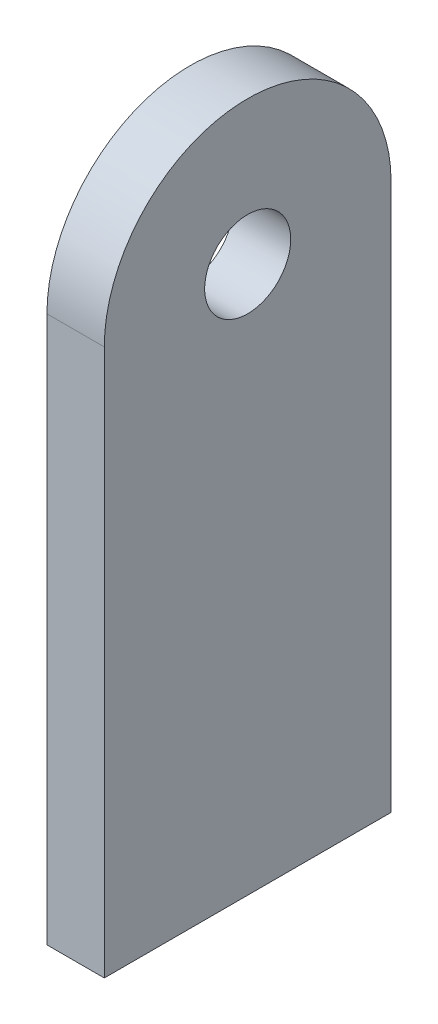
SolidWorks part; units mm, degrees
ref_plane "Front Plane" through (0, 0, 0) normal (0, 0, 1) x (1, 0, 0)
ref_plane "Top Plane" through (0, 0, 0) normal (0, 1, 0) x (1, 0, 0)
ref_plane "Right Plane" through (0, 0, 0) normal (1, 0, 0) x (0, 0, -1)
sketch "Sketch1" plane through (0, 0, 0) normal (1, 0, 0) x (0, 0, -1)
  line L0 (-25, -44.7227) -> (25, -44.7227)
  line L1 (-25, 50.5674) -> (-25, -44.7227)
  line L2 (25, 50.5674) -> (25, -44.7227)
  circle A0 centre (0, 50.5674) radius 7.5
  arc A1 (25, 50.5674) -> (-25, 50.5674) centre (0, 50.5674) ccw
  dimension "D1" = 15
  dimension "D2" = 50
  dimension "D3" = 95.2901
extrude "Boss-Extrude1" add sketch "Sketch1" along normal blind 10
